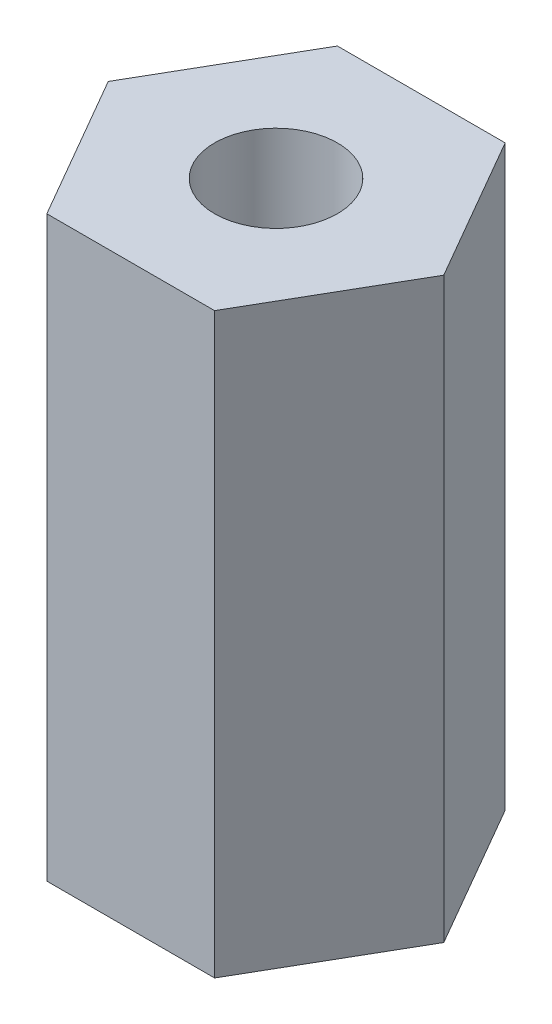
SolidWorks part; units mm, degrees
ref_plane "Front Plane" through (0, 0, 0) normal (0, 0, 1) x (1, 0, 0)
ref_plane "Top Plane" through (0, 0, 0) normal (0, 1, 0) x (1, 0, 0)
ref_plane "Right Plane" through (0, 0, 0) normal (1, 0, 0) x (0, 0, -1)
sketch "Sketch1" plane through (0, 0, 0) normal (0, 1, 0) x (1, 0, 0)
  line L1 (-3.695, 0) -> (-1.8475, -3.2)
  line L2 (-1.8475, -3.2) -> (1.8475, -3.2)
  line L3 (1.8475, -3.2) -> (3.695, 0)
  line L4 (3.695, 0) -> (1.8475, 3.2)
  line L5 (1.8475, 3.2) -> (-1.8475, 3.2)
  line L6 (-1.8475, 3.2) -> (-3.695, 0)
  circle A0 centre (0, 0) radius 3.2 construction
extrude "Boss-Extrude1" add sketch "Sketch1" along normal blind 12.73 contours L6 L1 L2 L3 L4 L5
sketch "Sketch3" plane through (0, 12.73, 0) normal (0, 1, 0) x (1, 0, 0)
  circle A0 centre (0, 0) radius 1.3525
extrude "Cut-Extrude1" cut sketch "Sketch3" against normal blind 6
sketch "Sketch4" plane through (0, 0, 0) normal (0, -1, 0) x (1, 0, 0)
  circle A0 centre (0, 0) radius 0.3535
extrude "Cut-Extrude2" cut sketch "Sketch4" against normal blind 1
